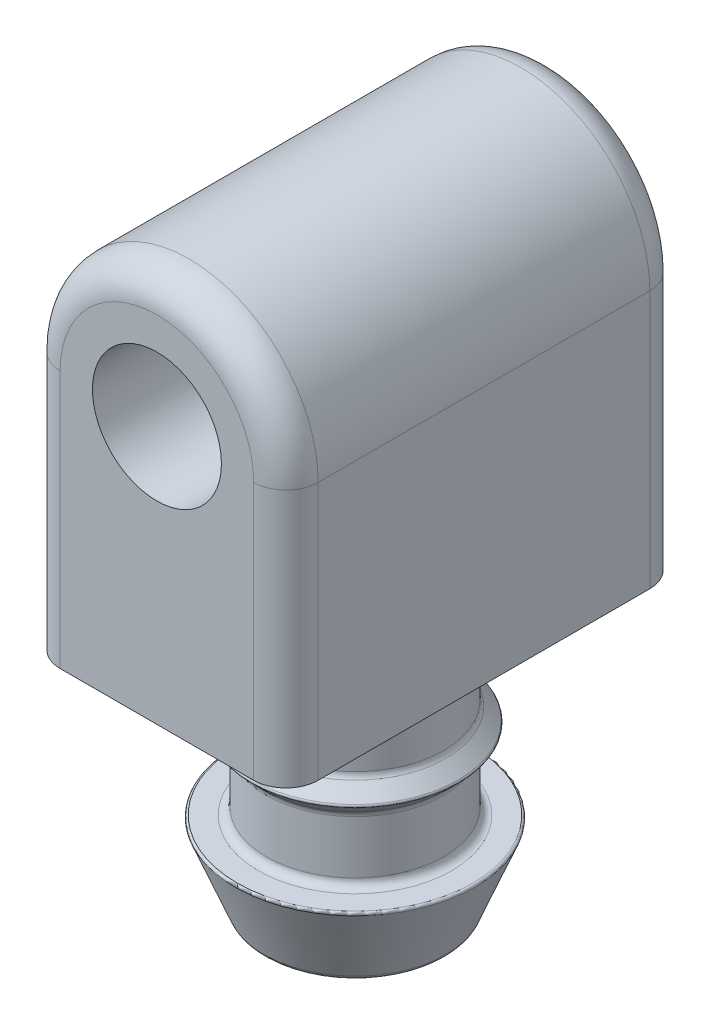
SolidWorks part; units mm, degrees
material "Oynx"
ref_plane "Front Plane" through (0, 0, 0) normal (0, 0, 1) x (1, 0, 0)
ref_plane "Top Plane" through (0, 0, 0) normal (0, 1, 0) x (1, 0, 0)
ref_plane "Right Plane" through (0, 0, 0) normal (1, 0, 0) x (0, 0, -1)
sketch "Sketch1" plane through (0, 0, 0) normal (0, 0, 1) x (1, 0, 0)
  line L0 (-6.35, 0) -> (-6.35, -12.7)
  line L1 (-6.35, -12.7) -> (6.35, -12.7)
  line L2 (6.35, -12.7) -> (6.35, 0)
  circle A0 centre (0, 0) radius 3.175
  arc A1 (6.35, 0) -> (-6.35, 0) centre (0, 0) ccw
  dimension "D1" = 6.35
  dimension "D2" = 12.7
  dimension "D3" = 12.7
extrude "Boss-Extrude1" add sketch "Sketch1" along normal mid plane 19.5
sketch "Sketch2" plane through (0, 0, 0) normal (0, 0, 1) x (1, 0, 0)
  line L0 (0, 9.544) -> (0, -9.544) construction
  line L1 (0, -12.7) -> (4.3656, -12.7)
  line L2 (-6.35, -12.7) -> (6.35, -12.7) construction
  line L4 (0, -25.4) -> (4.3656, -25.4)
  line L10 (0, -25.4) -> (0, -12.7)
  line L11 (4.3656, -25.4) -> (5.9531, -21.4312)
  line L12 (5.9531, -21.4312) -> (4.3656, -21.4312)
  line L13 (4.3656, -21.4312) -> (4.3656, -18.2562)
  line L14 (4.3656, -18.2562) -> (5.1594, -17.4625)
  line L15 (5.1594, -17.4625) -> (4.3656, -16.6687)
  line L16 (5.1594, -17.4625) -> (4.3656, -17.4625) construction
  line L17 (4.3656, -16.6687) -> (4.3656, -12.7)
  dimension "D1" = 8.7312
  dimension "D2" = 12.7
  dimension "D3" = 1.5875
  dimension "D4" = 3.9688
  dimension "D5" = 0.7937
  dimension "D6" = 7.9375
revolve "Revolve1" add sketch "Sketch2" angle 360 about L0
sketch "Sketch3" plane through (0, -25.4, 0) normal (0, -1, 0) x (1, 0, 0)
  circle A0 centre (0, 0) radius 2.3813
  dimension "D1" = 4.7625
extrude "Cut-Extrude1" cut sketch "Sketch3" against normal blind 20.6375 contours A0
fillet "Fillet1" radius 1.5875 7 edges at (-6.35, -6.35, -9.75) (0, 6.35, -9.75) (-6.35, -6.35, 9.75) (0, 6.35, 9.75) (6.35, -6.35, -9.75) (6.35, -6.35, 9.75) (2.3813, -4.7625, 0)
fillet "Fillet2" radius 0.3969 5 edges at (-4.3656, -21.4312, 0) (-4.3656, -25.4, 0) (-4.3656, -12.7, 0) (-4.3656, -18.2562, 0) (-4.3656, -16.6687, 0)
fillet "Fillet3" radius 0.0992 2 edges at (-5.9531, -21.4312, 0) (-5.1594, -17.4625, 0)
chamfer "Chamfer2" distance 0.254 angle 45 1 edges at (2.3813, -25.4, 0)
